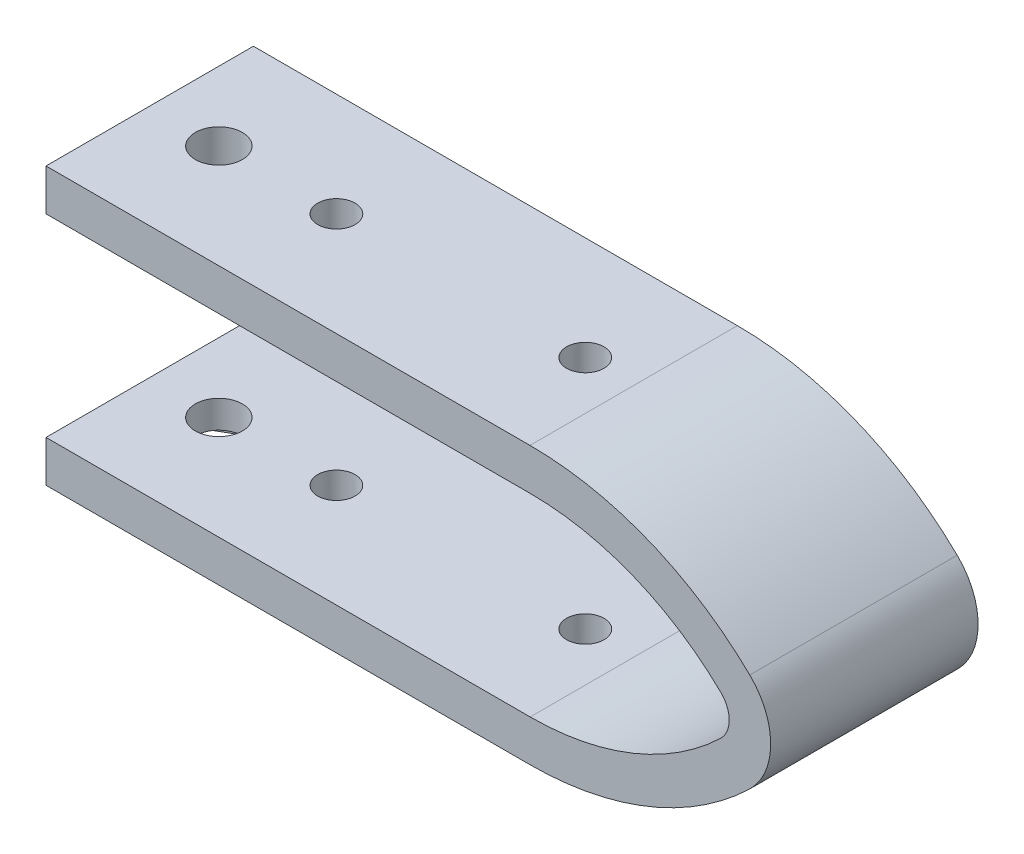
SolidWorks part; units mm, degrees
ref_plane "Front Plane" through (0, 0, 0) normal (0, 0, 1) x (1, 0, 0)
ref_plane "Top Plane" through (0, 0, 0) normal (0, 1, 0) x (1, 0, 0)
ref_plane "Right Plane" through (0, 0, 0) normal (1, 0, 0) x (0, 0, -1)
sketch "Sketch1" plane through (0, 0, 0) normal (0, 0, 1) x (1, 0, 0)
  line L0 (-2.5634, 10) -> (46.3243, 10) construction
  line L1 (0, 0) -> (35, 0)
  line L2 (0, 0) -> (0, 3)
  line L3 (0, 3) -> (35.0151, 3)
  line L6 (0, 17) -> (35.0151, 17)
  line L7 (0, 20) -> (0, 17)
  line L8 (0, 20) -> (35, 20)
  arc A0 (50.8963, 6.4313) -> (50.8963, 13.5687) centre (47.4435, 10) ccw
  arc A1 (35, 0) -> (50.8963, 6.4313) centre (35, 22.8611) ccw
  arc A2 (35.0151, 3) -> (48.7969, 8.5599) centre (35.0151, 22.8611) ccw
  arc A4 (48.7969, 11.4401) -> (48.7969, 8.5599) centre (47.4091, 10) cw
  arc A5 (35.0151, 17) -> (48.7969, 11.4401) centre (35.0151, -2.8611) cw
  arc A6 (35, 20) -> (50.8963, 13.5687) centre (35, -2.8611) cw
  dimension "D1" = 35
  dimension "D2" = 3
  dimension "D3" = 10
extrude "Boss-Extrude1" add sketch "Sketch1" along normal blind 15
sketch "Sketch2" plane through (0, 20, 0) normal (0, 1, 0) x (1, 0, 0)
  line L0 (0, -7.5) -> (46.5982, -7.5) construction
  line L1 (0, -15) -> (0, 0) construction
  line L2 (35, -15) -> (35, 0) construction
  circle A0 centre (5, -7.5) radius 1.7
  circle A1 centre (13.5, -7.5) radius 1.35
  circle A2 centre (31.5, -7.5) radius 1.35
  dimension "D1" = 3.4
  dimension "D2" = 2.7
  dimension "D3" = 5
  dimension "D4" = 13.5
  dimension "D5" = 3.5
extrude "Cut-Extrude1" cut sketch "Sketch2" against normal through all
sketch "Sketch3" plane through (0, 0, 0) normal (0, -1, 0) x (1, 0, 0)
  line L1 (5, 10.8486) -> (2.1, 9.1743)
  line L2 (2.1, 9.1743) -> (2.1, 5.8257)
  line L3 (2.1, 5.8257) -> (5, 4.1514)
  line L4 (5, 4.1514) -> (7.9, 5.8257)
  line L5 (7.9, 5.8257) -> (7.9, 9.1743)
  line L6 (7.9, 9.1743) -> (5, 10.8486)
  circle A0 centre (5, 7.5) radius 2.9 construction
  dimension "D1" = 5.8
extrude "Cut-Extrude2" cut sketch "Sketch3" against normal blind 1
